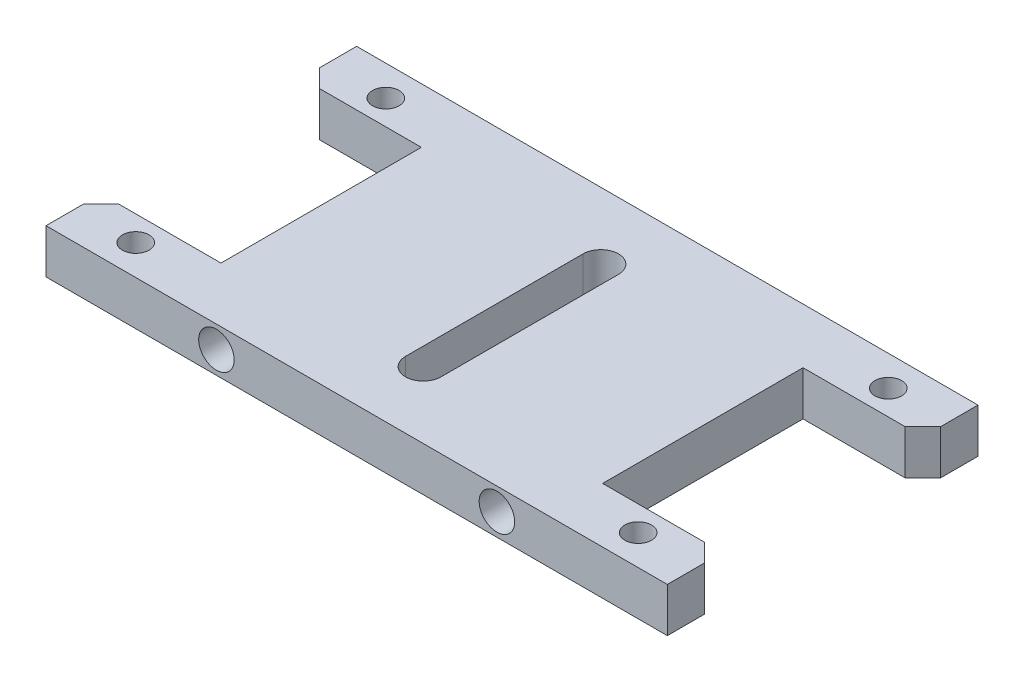
SolidWorks part; units mm, degrees
ref_plane "前视基准面" through (0, 0, 0) normal (0, 0, 1) x (1, 0, 0)
ref_plane "上视基准面" through (0, 0, 0) normal (0, 1, 0) x (1, 0, 0)
ref_plane "右视基准面" through (0, 0, 0) normal (1, 0, 0) x (0, 0, -1)
sketch "草图1" plane through (0, 0, 0) normal (0, 1, 0) x (1, 0, 0)
  line L0 (0, -1000.0249) -> (0, 48999.9751) construction
  line L9 (-35, 17.5) -> (35, 17.5)
  line L10 (-35, 17.5) -> (-35, -17.5)
  line L11 (-35, -17.5) -> (35, -17.5)
  line L12 (35, 17.5) -> (35, -17.5)
  line L13 (-35, 17.5) -> (35, -17.5) construction
  line L14 (-35, -17.5) -> (35, 17.5) construction
  line L18 (-21.5, 11.2886) -> (-21.5, -11.2886)
  line L24 (-35, -11.2886) -> (-35, 11.2886)
  line L32 (-21.5, 11.2886) -> (-35, 11.2886)
  line L33 (-21.5, -11.2886) -> (-35, -11.2886)
  line L34 (0, 0) -> (-50000, 0) construction
  line L35 (2, 10) -> (2, -10)
  line L36 (-2, 10) -> (-2, -10)
  line L37 (21.5, 11.2886) -> (21.5, -11.2886)
  line L38 (21.5, 11.2886) -> (35, 11.2886)
  line L39 (35, -11.2886) -> (35, 11.2886)
  line L40 (21.5, -11.2886) -> (35, -11.2886)
  circle A0 centre (-28.3037, 14.0886) radius 1.5
  circle A1 centre (-28.3037, -14.0886) radius 1.5
  circle A2 centre (28.3037, -14.0886) radius 1.5
  circle A3 centre (28.3037, 14.0886) radius 1.5
  arc A4 (2, 10) -> (-2, 10) centre (0, 10) ccw
  arc A5 (2, -10) -> (-2, -10) centre (0, -10) cw
  point P0 (0, 0)
  point P8 (-21.5, 0)
  dimension "D3" = 2.8
  dimension "D4" = 10
  dimension "D5" = 3
  dimension "D6" = 3.4114
  dimension "D7" = 6.6963
  dimension "D1" = 35
  dimension "D2" = 70
  dimension "D8" = 13.5
  dimension "D9" = 4
extrude "凸台-拉伸1" add sketch "草图1" along normal blind 5
chamfer "倒角1" distance 2 angle 45 4 edges at (-35, 2.5, 11.2886) (-35, 2.5, -11.2886) (35, 2.5, 11.2886) (35, 2.5, -11.2886)
sketch "草图2" plane through (0, 0, 17.5) normal (0, 0, 1) x (1, 0, 0)
  line L0 (0, 0) -> (0, 50000) construction
  line L1 (-35, 5) -> (-35, 0) construction
  circle A0 centre (-15.8, 2.5) radius 2
  circle A1 centre (15.8, 2.5) radius 2
  point P9 (-35, 2.5)
  dimension "D1" = 15.8
  dimension "D2" = 4
extrude "切除-拉伸1" cut sketch "草图2" against normal through all contours A1 | A0
